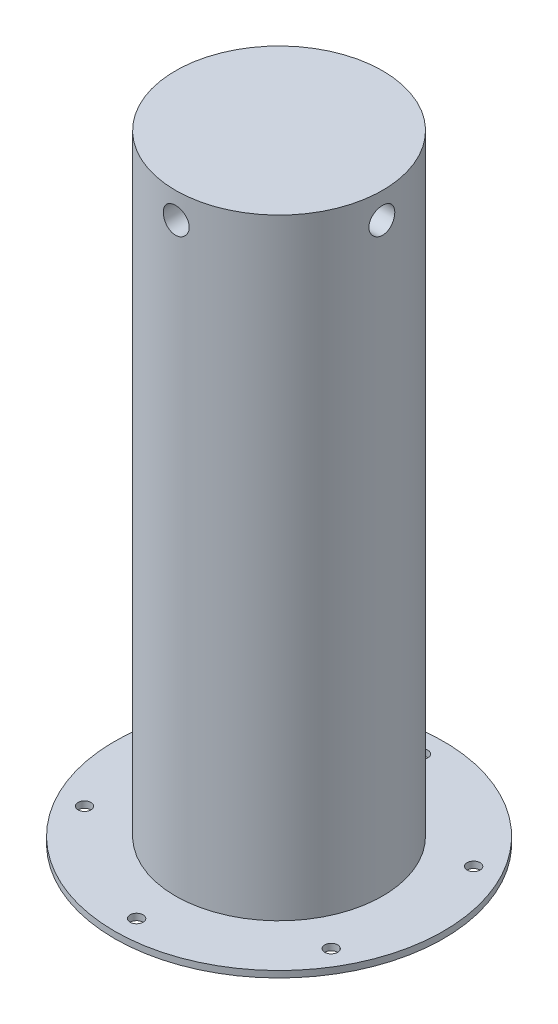
SolidWorks part; units mm, degrees
material "1060 Alloy"
ref_plane "Front Plane" through (0, 0, 0) normal (0, 0, 1) x (1, 0, 0)
ref_plane "Top Plane" through (0, 0, 0) normal (0, 1, 0) x (1, 0, 0)
ref_plane "Right Plane" through (0, 0, 0) normal (1, 0, 0) x (0, 0, -1)
sketch "Sketch2" plane through (0, 0, 0) normal (0, 0, 1) x (1, 0, 0)
  line L1 (101.6, 0) -> (101.6, 590.55)
  line L2 (101.6, 590.55) -> (0, 590.55)
  line L3 (0, 590.55) -> (0, 0)
  line L4 (101.6, 0) -> (161.29, 0)
  line L5 (161.29, 0) -> (161.29, -6.35)
  line L6 (161.29, -6.35) -> (0, -6.35)
  line L7 (0, -6.35) -> (0, 0)
  dimension "D1" = 101.6
  dimension "D2" = 590.55
  dimension "D3" = 59.69
  dimension "D4" = 6.35
revolve "Revolve1" add sketch "Sketch2" angle 360 about L3
sketch "Sketch4" plane through (0, 590.55, 0) normal (0, 1, 0) x (1, 0, 0)
  circle A0 centre (0, 0) radius 101.6
extrude "Boss-Extrude1" add sketch "Sketch4" along normal blind 8.89
sketch "Sketch5" plane through (0, 0, 0) normal (1, 0, 0) x (0, 0, -1)
  line L0 (101.6, 599.44) -> (-101.6, 599.44) construction
  circle A0 centre (0, 574.04) radius 12.7
  dimension "D1" = 25.4
  dimension "D2" = 25.4
extrude "Cut-Extrude2" cut sketch "Sketch5" against normal through all and the other way through all
sketch "Sketch6" plane through (0, 0, 0) normal (0, 0, 1) x (1, 0, 0)
  line L0 (101.6, 599.44) -> (-101.6, 599.44) construction
  circle A0 centre (0, 574.04) radius 12.7
  dimension "D1" = 25.4
  dimension "D2" = 25.4
extrude "Cut-Extrude3" cut sketch "Sketch6" against normal through all and the other way through all
sketch "Sketch7" plane through (0, -6.35, 0) normal (0, -1, 0) x (1, 0, 0)
  circle A0 centre (0, 0) radius 139.7
  circle A1 centre (0, 139.7) radius 6.35
  circle A2 centre (120.9837, 69.85) radius 6.35
  circle A3 centre (120.9837, -69.85) radius 6.35
  circle A4 centre (0, -139.7) radius 6.35
  circle A5 centre (-120.9837, -69.85) radius 6.35
  circle A6 centre (-120.9837, 69.85) radius 6.35
  point P17 (0, 0)
  dimension "D1" = 279.4
  dimension "D2" = 12.7
  dimension "D3" = 6
extrude "Cut-Extrude4" cut sketch "Sketch7" against normal through all contours A1 | A6 | A2 | A3 | A4 | A5
